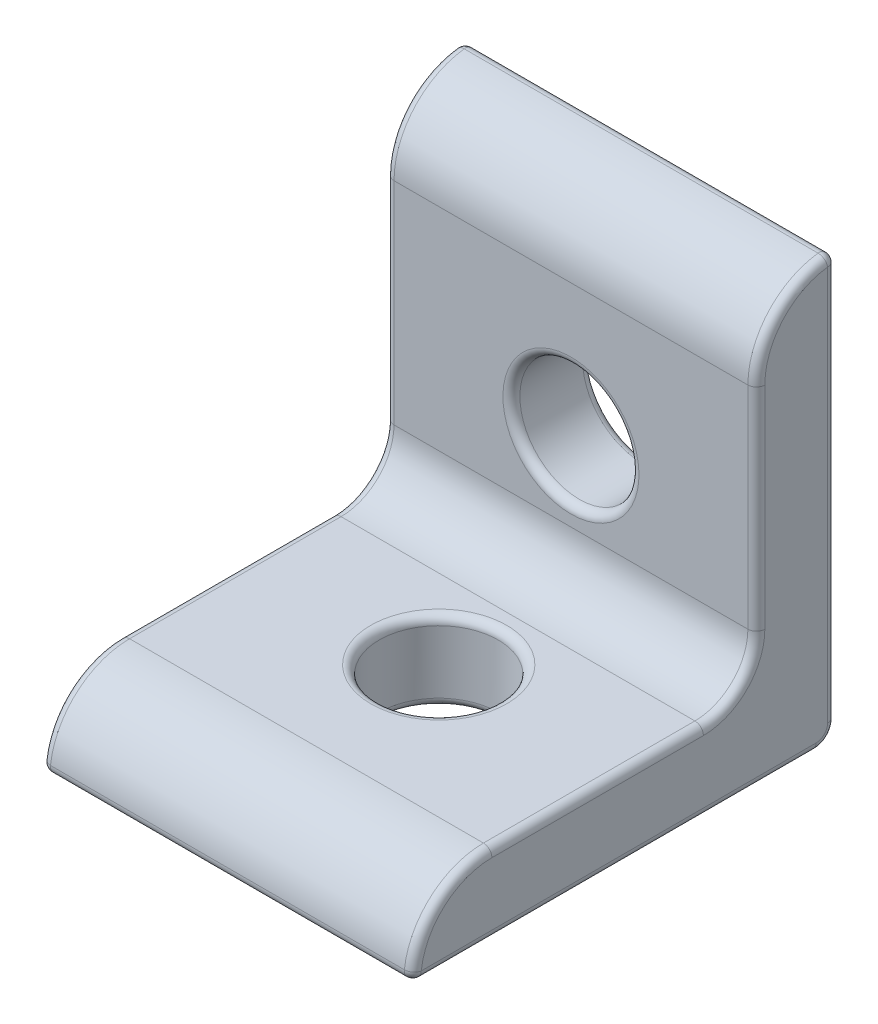
SolidWorks part; units mm, degrees
ref_plane "Front Plane" through (0, 0, 0) normal (0, 0, 1) x (1, 0, 0)
ref_plane "Top Plane" through (0, 0, 0) normal (0, 1, 0) x (1, 0, 0)
ref_plane "Right Plane" through (0, 0, 0) normal (1, 0, 0) x (0, 0, -1)
sketch "Sketch1" plane through (0, 0, 0) normal (0, 0, 1) x (1, 0, 0)
  line L0 (-11.1125, -12.7) -> (11.1125, -12.7) construction
  line L1 (0, -12.7) -> (0, 12.7) construction
  line L2 (-11.1125, 12.7) -> (11.1125, 12.7) construction
  dimension "Width" = 22.225
  dimension "Length" = 25.4
sketch "Sketch2" plane through (0, 0, 0) normal (1, 0, 0) x (0, 0, -1)
  line L0 (-20.6248, -12.7) -> (4.7752, -12.7) construction
  line L1 (0, -12.7) -> (0, 12.7) construction
  line L2 (4.7752, -12.7) -> (4.7752, 12.7) construction
  line L3 (0, 7.9248) -> (0, -4.7498)
  line L4 (-3.175, -7.9248) -> (-15.8496, -7.9248)
  line L5 (4.7752, 0) -> (0, 0) construction
  line L6 (-7.9248, -12.7) -> (-7.9248, -7.9248) construction
  line L7 (4.7752, 3.5687) -> (4.7752, -3.5687)
  line L8 (-11.4935, -12.7) -> (-4.3561, -12.7)
  line L9 (4.7752, 0) -> (12.7, 0) construction
  line L10 (12.7, 3.175) -> (12.7, -3.175) construction
  line L11 (12.7, 3.175) -> (13.97, 3.175) construction
  arc A0 (4.7752, 12.7) -> (0, 7.9248) centre (4.7752, 7.9248) ccw
  arc A1 (0, -4.7498) -> (-3.175, -7.9248) centre (-3.175, -4.7498) cw
  arc A2 (-15.8496, -7.9248) -> (-20.6248, -12.7) centre (-15.8496, -12.7) ccw
  dimension "Bracket End Radius" = 4.7752
  dimension "Bracket Corner Radius" = 3.175
  dimension "D1" = 25.4
  dimension "Bracket Thickness" = 4.7752
  dimension "Mounting Hole Diameter" = 7.1374
  dimension "Mounting Hole Offset" = 12.7
  dimension "D3" = 12.7
  dimension "Mounting Fastener Thread Length" = 12.7
  dimension "Mounting Fastener Thread Size" = 6.35
  dimension "Mounting Fastener Thread Pitch" = 1.27
sketch "Sketch3" plane through (0, 0, 0) normal (1, 0, 0) x (0, 0, -1)
  line L0 (-3.175, -7.9248) -> (-15.8496, -7.9248) construction
  line L1 (0, 7.9248) -> (0, -4.7498) construction
  line L2 (-3.175, -7.9248) -> (-15.8496, -7.9248)
  line L3 (0, 7.9248) -> (0, -4.7498)
  line L4 (-20.6248, -12.7) -> (4.7752, -12.7)
  line L5 (4.7752, -12.7) -> (4.7752, 12.7)
  arc A0 (-15.8496, -7.9248) -> (-20.6248, -12.7) centre (-15.8496, -12.7) ccw construction
  arc A1 (-3.175, -7.9248) -> (0, -4.7498) centre (-3.175, -4.7498) ccw construction
  arc A2 (4.7752, 12.7) -> (0, 7.9248) centre (4.7752, 7.9248) ccw construction
  arc A3 (-15.8496, -7.9248) -> (-20.6248, -12.7) centre (-15.8496, -12.7) ccw
  arc A4 (-3.175, -7.9248) -> (0, -4.7498) centre (-3.175, -4.7498) ccw
  arc A5 (4.7752, 12.7) -> (0, 7.9248) centre (4.7752, 7.9248) ccw
extrude "Boss-Extrude1" add sketch "Sketch3" against normal up to vertex (11.1125 mm away) from vertex at 11.1125 starting at point (11.1125, -12.7, 0)
fillet "Fillet1" radius 1.1938 1 edges at (0, -12.7, -4.7752)
sketch "Sketch4" plane through (0, 0, 0) normal (0, 0, 1) x (1, 0, 0)
  circle A0 centre (0, 0) radius 3.5687
extrude "Cut-Extrude1" cut sketch "Sketch4" against normal through all
sketch "Sketch5" plane through (0, -7.9248, 0) normal (0, 1, 0) x (1, 0, 0)
  circle A0 centre (0, -7.9248) radius 3.5687
extrude "Cut-Extrude2" cut sketch "Sketch5" against normal through all
fillet "Fillet2" radius 0.508 19 edges at (-11.1125, -12.7, 8.5217) (-11.1125, -12.3503, -4.4255) (11.1125, -12.7, 8.5217) (11.1125, -12.3503, -4.4255) (-11.1125, -9.3234, 19.2262) (-11.1125, -7.9248, 9.5123) (-11.1125, -6.9949, 0.9299) (-11.1125, 1.5875, 0) (11.1125, -9.3234, 19.2262) (11.1125, -7.9248, 9.5123) (11.1125, -6.9949, 0.9299) (11.1125, 1.5875, 0) (0, -12.7, 20.6248) (0, 12.7, -4.7752) (-11.1125, 0.5969, -4.7752) (11.1125, 0.5969, -4.7752) (-11.1125, 11.3014, -1.3986) (11.1125, 11.3014, -1.3986) (0, -12.7, 11.4935)
fillet "Fillet3" radius 0.508 3 edges at (0, -7.9248, 11.4935) (3.5687, 0, 0) (3.5687, 0, -4.7752)
equation "\"D3@Sketch2\" = \"Mounting Hole Offset@Sketch2\""
equation "\"D1@Fillet1\"=\"Bracket End Radius@Sketch2\"/4"
equation "\"Bracket End Radius@Sketch2\"=\"Bracket Thickness@Sketch2\""
equation "\"D1@Sketch2\"=\"Length@Sketch1\""
